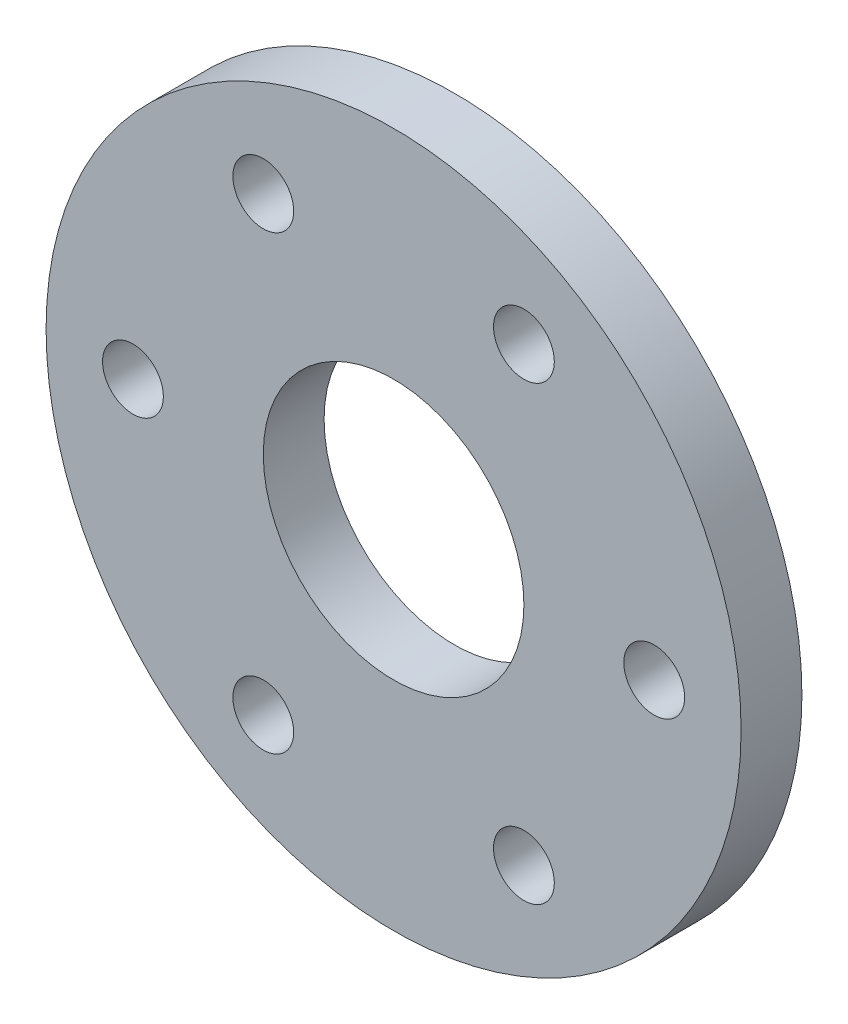
SolidWorks part; units mm, degrees
ref_plane "前视基准面" through (0, 0, 0) normal (0, 0, 1) x (1, 0, 0)
ref_plane "上视基准面" through (0, 0, 0) normal (0, 1, 0) x (1, 0, 0)
ref_plane "右视基准面" through (0, 0, 0) normal (1, 0, 0) x (0, 0, -1)
sketch "草图1" plane through (0, 0, 0) normal (0, 0, 1) x (1, 0, 0)
  circle A0 centre (0, 0) radius 80
  circle A1 centre (0, 0) radius 30
  circle A2 centre (60, 0) radius 7
  circle A3 centre (30, 51.9615) radius 7
  circle A4 centre (-30, 51.9615) radius 7
  circle A5 centre (-60, 0) radius 7
  circle A6 centre (-30, -51.9615) radius 7
  circle A7 centre (30, -51.9615) radius 7
extrude "凸台-拉伸1" add sketch "草图1" along normal blind 14
